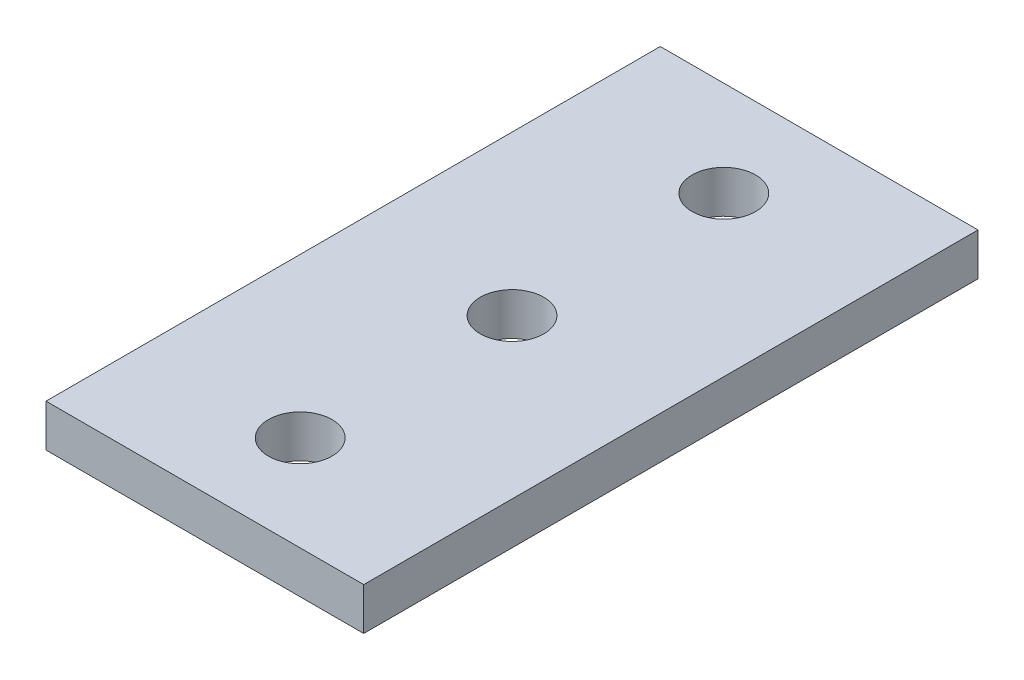
SolidWorks part; units mm, degrees
ref_plane "Front Plane" through (0, 0, 0) normal (0, 0, 1) x (1, 0, 0)
ref_plane "Top Plane" through (0, 0, 0) normal (0, 1, 0) x (1, 0, 0)
ref_plane "Right Plane" through (0, 0, 0) normal (1, 0, 0) x (0, 0, -1)
sketch "Sketch1" plane through (0, 0, 0) normal (0, 1, 0) x (1, 0, 0)
  line L1 (0, 0) -> (15, 0)
  line L2 (0, 0) -> (0, 29)
  line L3 (0, 29) -> (15, 29)
  line L4 (15, 0) -> (15, 29)
  circle A0 centre (7.5, 24.5) radius 1.5
  circle A1 centre (7.5, 14.5) radius 1.5
  circle A2 centre (7.5, 4.5) radius 1.5
  dimension "D3" = 4.5
  dimension "D1" = 15
  dimension "D2" = 29
  dimension "D4" = 4.5
  dimension "D5" = 14.5
  dimension "D6" = 24.5
extrude "Boss-Extrude1" add sketch "Sketch1" along normal blind 2
sketch "Sketch2" plane through (0, 2, 0) normal (0, 1, 0) x (1, 0, 0)
  circle A0 centre (7.5, 14.5) radius 5
